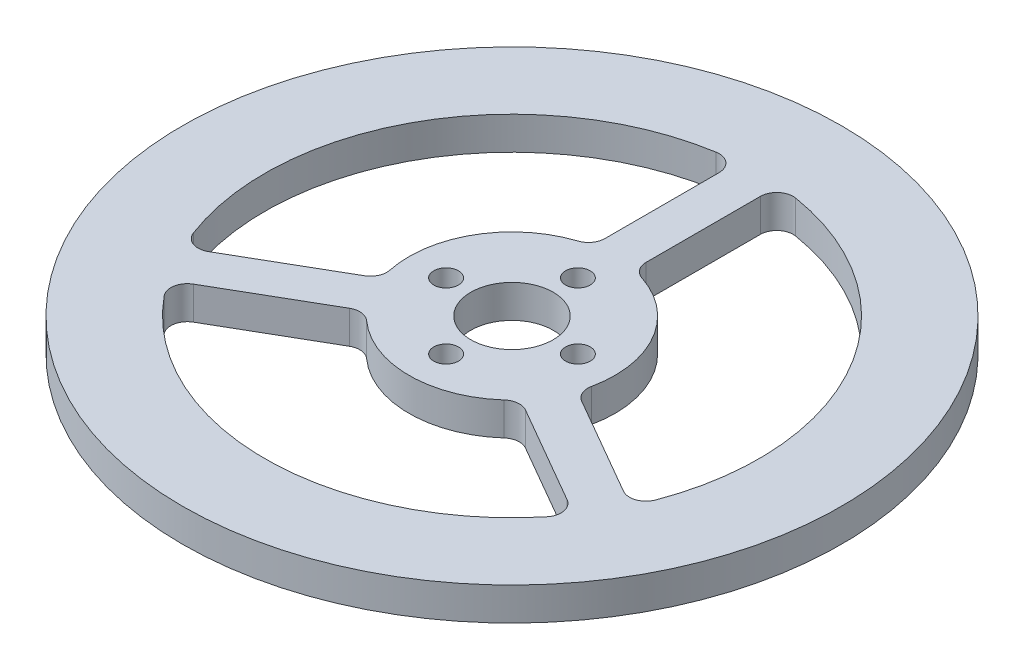
SolidWorks part; units mm, degrees
material "1060-H12 Vareta (SS)"
ref_plane "Plano frontal" through (0, 0, 0) normal (0, 0, 1) x (1, 0, 0)
ref_plane "Plano superior" through (0, 0, 0) normal (0, 1, 0) x (1, 0, 0)
ref_plane "Plano direito" through (0, 0, 0) normal (1, 0, 0) x (0, 0, -1)
ref_plane "Plano1" through (0, 4, 0) normal (0, 1, 0) x (1, 0, 0)
sketch "Esboço1" plane through (0, 4, 0) normal (0, 1, 0) x (1, 0, 0)
  line L0 (-2.5, 27.636) -> (-2.5, 13.784)
  line L1 (-13.1873, -4.727) -> (-25.1835, -11.653)
  line L2 (25.1835, -11.653) -> (13.1873, -4.727)
  line L3 (2.5, 13.784) -> (2.5, 27.636)
  line L4 (10.6873, -9.0571) -> (22.6835, -15.9831)
  line L5 (-22.6835, -15.9831) -> (-10.6873, -9.0571)
  circle A0 centre (-8, 0) radius 1.5
  circle A1 centre (0, -8) radius 1.5
  circle A2 centre (8, 0) radius 1.5
  circle A3 centre (0, 8) radius 1.5
  circle A4 centre (0, 0) radius 5
  arc A5 (-2.5, 13.784) -> (-3.8793, 11.8828) centre (-4.5, 13.784) cw
  arc A6 (-3.8793, 11.8828) -> (-12.2305, -2.5818) centre (0, 0) ccw
  arc A7 (-12.2305, -2.5818) -> (-13.1873, -4.727) centre (-14.1873, -2.9949) cw
  arc A8 (-25.1835, -11.653) -> (-28.0538, -10.6295) centre (-26.1835, -9.9209) cw
  arc A9 (-28.0538, -10.6295) -> (-4.8214, 29.61) centre (0, 0) cw
  arc A10 (-4.8214, 29.61) -> (-2.5, 27.636) centre (-4.5, 27.636) cw
  circle A11 centre (0, 0) radius 40
  arc A12 (13.1873, -4.727) -> (12.2305, -2.5818) centre (14.1873, -2.9949) cw
  arc A13 (12.2305, -2.5818) -> (3.8793, 11.8828) centre (0, 0) ccw
  arc A14 (3.8793, 11.8828) -> (2.5, 13.784) centre (4.5, 13.784) cw
  arc A15 (2.5, 27.636) -> (4.8214, 29.61) centre (4.5, 27.636) cw
  arc A16 (4.8214, 29.61) -> (28.0538, -10.6295) centre (0, 0) cw
  arc A17 (28.0538, -10.6295) -> (25.1835, -11.653) centre (26.1835, -9.9209) cw
  arc A18 (22.6835, -15.9831) -> (23.2323, -18.9805) centre (21.6835, -17.7151) cw
  arc A19 (23.2323, -18.9805) -> (-23.2323, -18.9805) centre (0, 0) cw
  arc A20 (-23.2323, -18.9805) -> (-22.6835, -15.9831) centre (-21.6835, -17.7151) cw
  arc A21 (-10.6873, -9.0571) -> (-8.3512, -9.301) centre (-9.6873, -10.7891) cw
  arc A22 (-8.3512, -9.301) -> (8.3512, -9.301) centre (0, 0) ccw
  arc A23 (8.3512, -9.301) -> (10.6873, -9.0571) centre (9.6873, -10.7891) cw
extrude "Ressalto-extrusão1" add sketch "Esboço1" against normal blind 4
